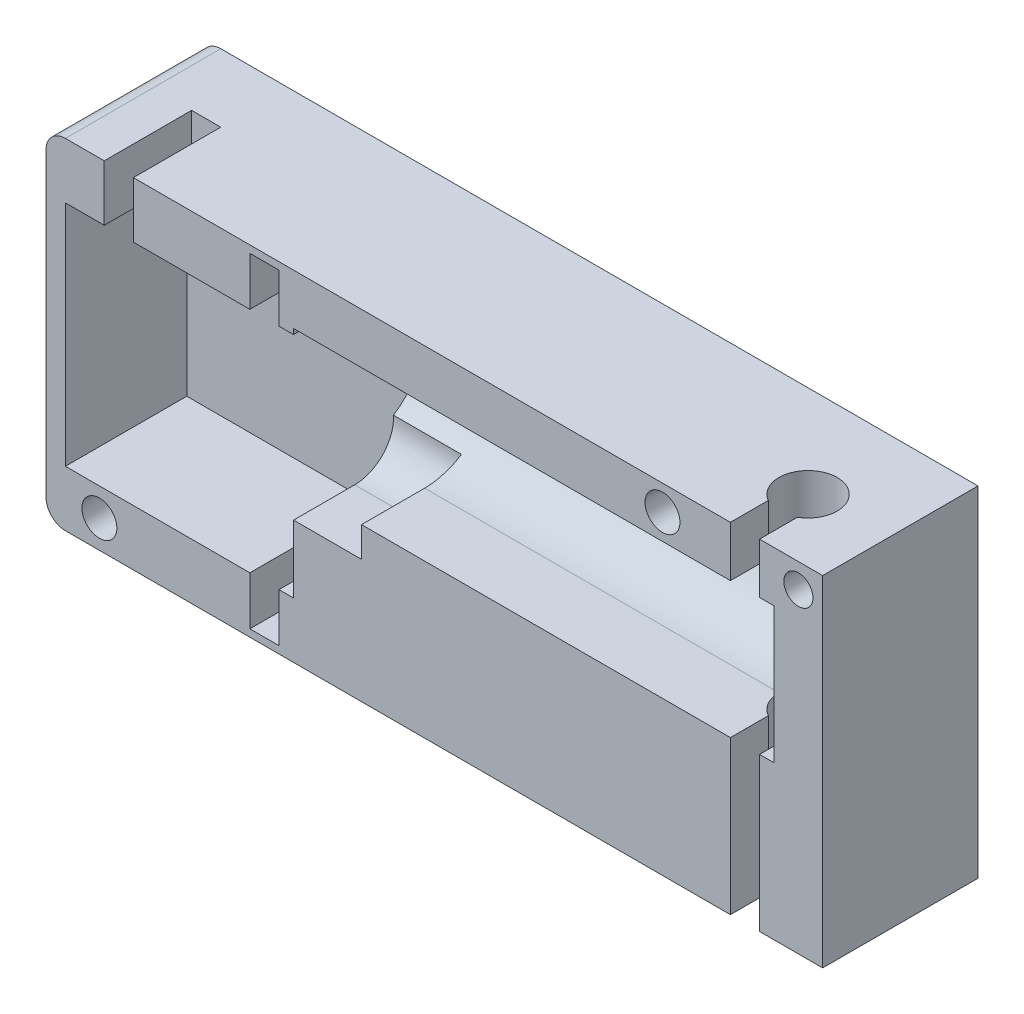
SolidWorks part; units mm, degrees
ref_plane "Front Plane" through (0, 0, 0) normal (0, 0, 1) x (1, 0, 0)
ref_plane "Top Plane" through (0, 0, 0) normal (0, 1, 0) x (1, 0, 0)
ref_plane "Right Plane" through (0, 0, 0) normal (1, 0, 0) x (0, 0, -1)
sketch "Sketch1" plane through (0, 0, 0) normal (0, 0, 1) x (1, 0, 0)
  line L0 (8.7404, -4.0789) -> (8.7404, 4.0789)
  line L1 (-37.5, 17.5) -> (37.5, 17.5)
  line L2 (-37.5, 17.5) -> (-37.5, -17.5)
  line L3 (-37.5, -17.5) -> (37.5, -17.5)
  line L4 (37.5, 17.5) -> (37.5, -17.5)
  line L5 (-37.5, 17.5) -> (37.5, -17.5) construction
  line L6 (-37.5, -17.5) -> (37.5, 17.5) construction
  line L10 (10.2694, 4.7924) -> (10.2694, -4.7924)
  point P0 (0, 0)
  dimension "D1" = 35
  dimension "D2" = 75
extrude "Boss-Extrude5" add sketch "Sketch1" along normal blind 16
sketch "Sketch2" plane through (0, 0, 16) normal (0, 0, 1) x (1, 0, 0)
  line L0 (-37.5, 17.5) -> (-37.5, -17.5) construction
  line L1 (-35.5, 11.75) -> (-16.5, 11.75)
  line L2 (-35.5, 11.75) -> (-35.5, -11.75)
  line L3 (-35.5, -11.75) -> (-16.5, -11.75)
  line L4 (-12, 11.75) -> (-12, -11.75)
  line L5 (-37.5, -17.5) -> (37.5, -17.5) construction
  line L7 (-13.5, -11.75) -> (-13.5, -16.75)
  line L8 (-16.5, 16.75) -> (-13.5, 16.75)
  line L9 (-16.5, 16.75) -> (-16.5, 11.75)
  line L10 (-16.5, -16.75) -> (-13.5, -16.75)
  line L11 (-13.5, 16.75) -> (-13.5, 11.75)
  line L12 (-16.5, -11.75) -> (-16.5, -16.75)
  line L13 (-13.5, -11.75) -> (-12, -11.75)
  line L14 (-13.5, 11.75) -> (-12, 11.75)
  dimension "D1" = 23.5
  dimension "D2" = 23.5
  dimension "D3" = 2
  dimension "D4" = 5.75
  dimension "D5" = 3
  dimension "D6" = 5
  dimension "D7" = 5
  dimension "D8" = 19
extrude "Cut-Extrude1" cut sketch "Sketch2" against normal blind 12.5 contours L1 L9 L8 L11 L14 L4 L13 L7 L10 L12 L3 L2
sketch "Sketch3" plane through (-12, 0, 0) normal (-1, 0, 0) x (0, 0, 1)
  line L0 (9.5, 12.2967) -> (16, 12.2967)
  line L1 (16, 12.2967) -> (16, -1.7033)
  line L2 (16, 11.75) -> (16, -11.75) construction
  line L3 (16, -1.7033) -> (9.5, -1.7033)
  arc A0 (9.5, 12.2967) -> (9.5, -1.7033) centre (9.5, 5.2967) ccw
  dimension "D1" = 7
extrude "Cut-Extrude2" cut sketch "Sketch3" against normal up to next
sketch "Sketch5" plane through (-12, 0, 0) normal (-1, 0, 0) x (0, 0, 1)
  line L0 (9.702, -4.8) -> (16, -4.8)
  line L1 (16, 17.5) -> (16, -17.5) construction
  line L2 (16, -4.8) -> (16, 3.2)
  line L3 (16, 12.2967) -> (16, -1.7033) construction
  line L4 (16, 3.2) -> (9.702, 3.2)
  arc A0 (9.702, 3.2) -> (9.702, -4.8) centre (9.702, -0.8) ccw
  dimension "D1" = 8
  dimension "D2" = 6.1
extrude "Cut-Extrude3" cut sketch "Sketch5" against normal blind 7
sketch "Sketch6" plane through (37.5, 0, 0) normal (1, 0, 0) x (0, 0, -1)
  line L1 (-16, -17.5) -> (0, -17.5)
  line L2 (-16, -17.5) -> (-16, 17.5)
  line L3 (-16, 17.5) -> (0, 17.5)
  line L4 (0, -17.5) -> (0, 17.5)
extrude "Boss-Extrude6" add sketch "Sketch6" along normal blind 5
sketch "Sketch7" plane through (0, -17.5, 0) normal (0, -1, 0) x (1, 0, 0)
  line L0 (34.4967, 9.5) -> (34.4967, 16) construction
  line L1 (37.5, 9.5) -> (-5, 9.5) construction
  line L3 (32.9967, 12.0981) -> (32.9967, 16)
  line L7 (32.9967, 16) -> (35.9967, 16)
  line L8 (35.9967, 16) -> (35.9967, 12.0981)
  line L9 (32.9967, 12.0981) -> (34.4967, 9.5) construction
  line L10 (34.4967, 9.5) -> (35.9967, 12.0981) construction
  arc A1 (35.9967, 12.0981) -> (32.9967, 12.0981) centre (34.4967, 9.5) cw
  dimension "D1" = 30
  dimension "D2" = 3
extrude "Cut-Extrude4" cut sketch "Sketch7" against normal through all
sketch "Sketch8" plane through (0, 0, 16) normal (0, 0, 1) x (1, 0, 0)
  circle A0 centre (40, 15) radius 1.5
  dimension "D1" = 3
extrude "Cut-Extrude5" cut sketch "Sketch8" against normal blind 13
sketch "Sketch10" plane through (0, 0, 16) normal (0, 0, 1) x (1, 0, 0)
  line L0 (-35.5, 11.75) -> (-16.5, 11.75) construction
  line L1 (-31.5, 11.75) -> (-28.5, 11.75)
  line L2 (-31.5, 11.75) -> (-31.5, 17.5)
  line L3 (-31.5, 17.5) -> (-28.5, 17.5)
  line L4 (-28.5, 11.75) -> (-28.5, 17.5)
  line L5 (-37.5, 17.5) -> (32.9967, 17.5) construction
  line L6 (-35.5, 11.75) -> (-35.5, -11.75) construction
  dimension "D1" = 4
  dimension "D2" = 3
extrude "Cut-Extrude6" cut sketch "Sketch10" against normal blind 9
fillet "Fillet1" radius 2 2 edges at (-37.5, 17.5, 8) (-37.5, -17.5, 8)
sketch "Sketch11" plane through (0, 0, 16) normal (0, 0, 1) x (1, 0, 0)
  circle A0 centre (-32, -14.625) radius 1.8
  circle A1 centre (26, 14.8983) radius 1.8
extrude "Cut-Extrude7" cut sketch "Sketch11" against normal blind 12
